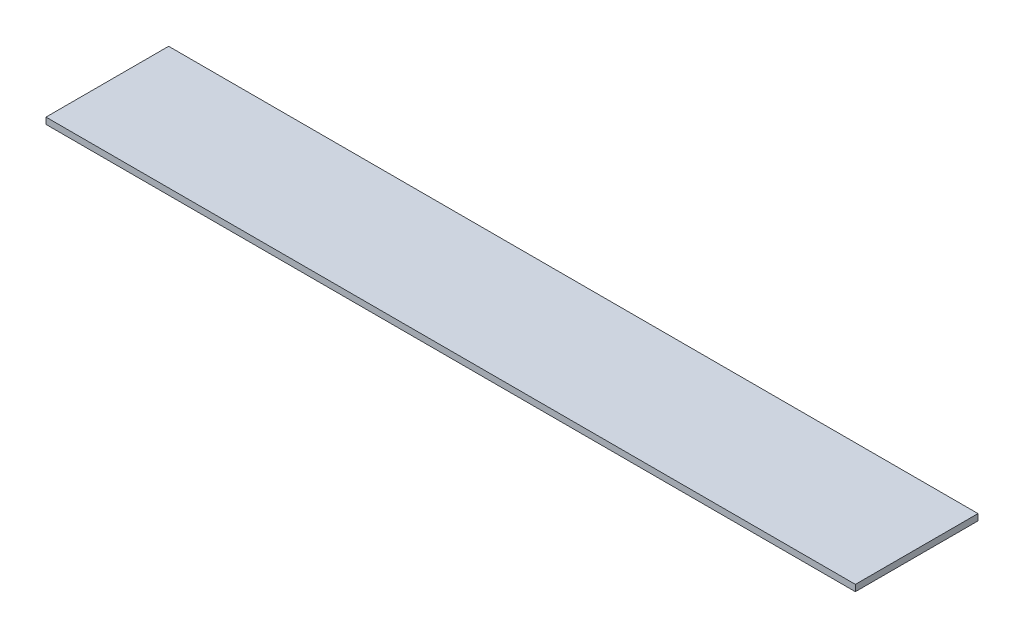
SolidWorks part; units mm, degrees
material "Cedar"
ref_plane "Front Plane" through (0, 0, 0) normal (0, 0, 1) x (1, 0, 0)
ref_plane "Top Plane" through (0, 0, 0) normal (0, 1, 0) x (1, 0, 0)
ref_plane "Right Plane" through (0, 0, 0) normal (1, 0, 0) x (0, 0, -1)
sketch "Sketch1" plane through (0, 0, 0) normal (0, 1, 0) x (1, 0, 0)
  line L1 (-314.325, -47.625) -> (314.325, -47.625)
  line L2 (-314.325, -47.625) -> (-314.325, 47.625)
  line L3 (-314.325, 47.625) -> (314.325, 47.625)
  line L4 (314.325, -47.625) -> (314.325, 47.625)
  line L5 (-314.325, -47.625) -> (314.325, 47.625) construction
  line L6 (-314.325, 47.625) -> (314.325, -47.625) construction
  point P0 (0, 0)
  dimension "D1" = 628.65
  dimension "D2" = 95.25
extrude "Boss-Extrude1" add sketch "Sketch1" along normal blind 4.953
